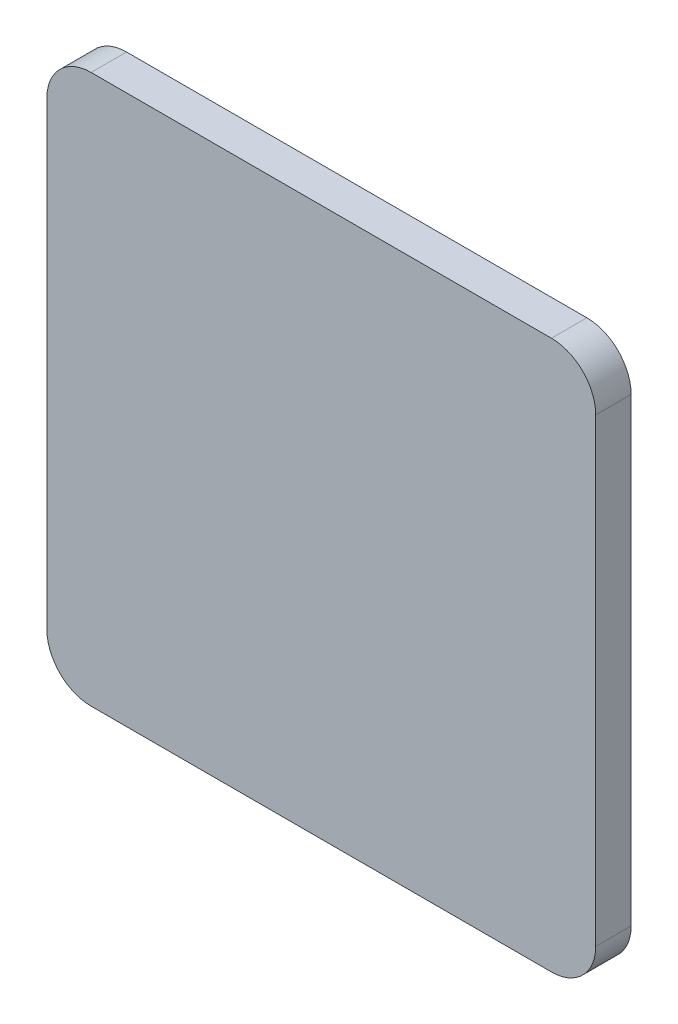
SolidWorks part; units mm, degrees
ref_plane "Piano frontale" through (0, 0, 0) normal (0, 0, 1) x (1, 0, 0)
ref_plane "Piano superiore" through (0, 0, 0) normal (0, 1, 0) x (1, 0, 0)
ref_plane "Piano destro" through (0, 0, 0) normal (1, 0, 0) x (0, 0, -1)
sketch "Schizzo1" plane through (0, 0, 0) normal (0, 0, 1) x (1, 0, 0)
  line L5 (-37.2086, -35.2974) -> (-63.2086, -35.2974) construction
  line L6 (-34.7086, -6.7974) -> (-34.7086, -32.7974) construction
  line L7 (-63.2086, -4.2974) -> (-37.2086, -4.2974) construction
  line L8 (-65.7086, -32.7974) -> (-65.7086, -6.7974) construction
  line L9 (-37.2086, -35.2974) -> (-63.2086, -35.2974)
  line L10 (-34.7086, -6.7974) -> (-34.7086, -32.7974)
  line L11 (-63.2086, -4.2974) -> (-37.2086, -4.2974)
  line L12 (-65.7086, -32.7974) -> (-65.7086, -6.7974)
  arc A0 (-65.7086, -32.7974) -> (-63.2086, -35.2974) centre (-63.2086, -32.7974) ccw construction
  arc A1 (-37.2086, -35.2974) -> (-34.7086, -32.7974) centre (-37.2086, -32.7974) ccw construction
  arc A2 (-34.7086, -6.7974) -> (-37.2086, -4.2974) centre (-37.2086, -6.7974) ccw construction
  arc A3 (-63.2086, -4.2974) -> (-65.7086, -6.7974) centre (-63.2086, -6.7974) ccw construction
  arc A4 (-65.7086, -32.7974) -> (-63.2086, -35.2974) centre (-63.2086, -32.7974) ccw
  arc A5 (-37.2086, -35.2974) -> (-34.7086, -32.7974) centre (-37.2086, -32.7974) ccw
  arc A6 (-34.7086, -6.7974) -> (-37.2086, -4.2974) centre (-37.2086, -6.7974) ccw
  arc A7 (-63.2086, -4.2974) -> (-65.7086, -6.7974) centre (-63.2086, -6.7974) ccw
  point P6 (-14.6234, 11.0945)
  point P7 (0, 0)
  point P8 (13.8766, -14.1734)
extrude "Estrusione-Estrusione1" add sketch "Schizzo1" along normal blind 2
